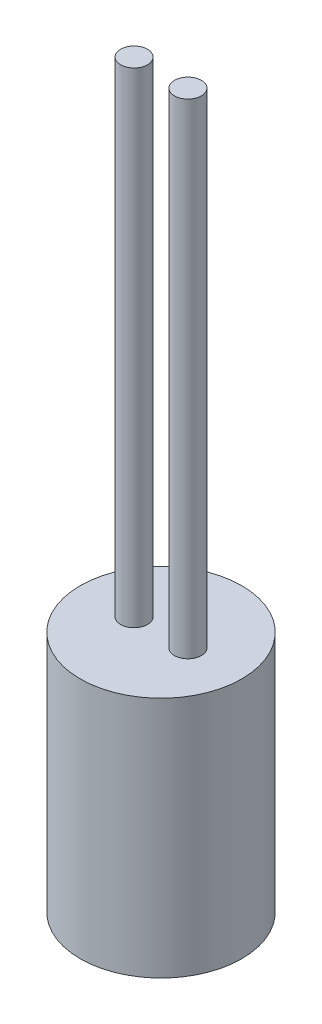
SolidWorks part; units mm, degrees
ref_plane "Front Plane" through (0, 0, 0) normal (0, 0, 1) x (1, 0, 0)
ref_plane "Top Plane" through (0, 0, 0) normal (0, 1, 0) x (1, 0, 0)
ref_plane "Right Plane" through (0, 0, 0) normal (1, 0, 0) x (0, 0, -1)
sketch "Sketch1" plane through (0, 0, 0) normal (0, 1, 0) x (1, 0, 0)
  circle A0 centre (0, 0) radius 3
  point P3 (-212.7268, -35.3416)
extrude "Head" add sketch "Sketch1" against normal blind 9
sketch "Sketch2" plane through (0, 0, 0) normal (0, 1, 0) x (1, 0, 0)
  circle A1 centre (-1, 0) radius 0.5
  circle A2 centre (1, 0) radius 0.5
extrude "Pins" add sketch "Sketch2" along normal blind 18
